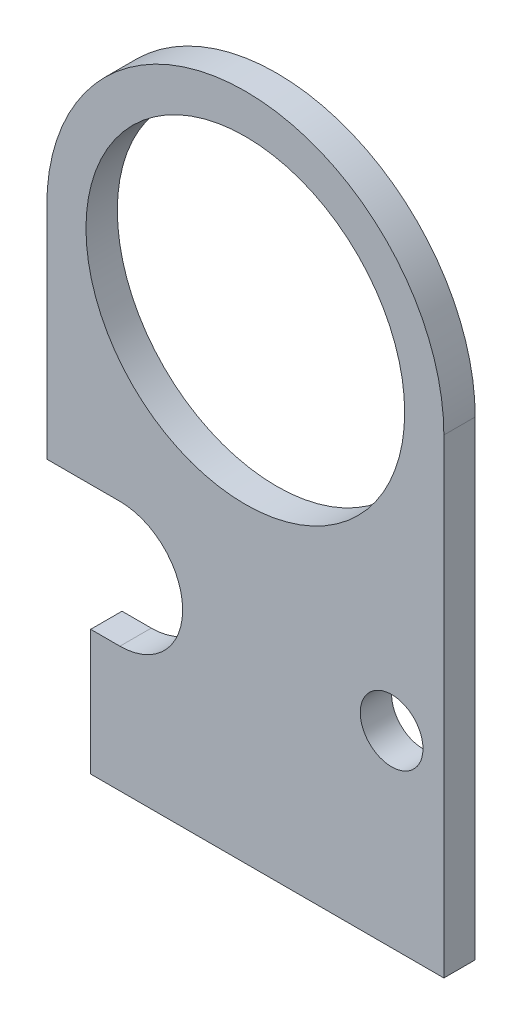
SolidWorks part; units mm, degrees
material "Foam"
ref_plane "Front Plane" through (0, 0, 0) normal (0, 0, 1) x (1, 0, 0)
ref_plane "Top Plane" through (0, 0, 0) normal (0, 1, 0) x (1, 0, 0)
ref_plane "Right Plane" through (0, 0, 0) normal (1, 0, 0) x (0, 0, -1)
sketch "Sketch1" plane through (0, 0, 0) normal (0, 0, 1) x (1, 0, 0)
  line L0 (-19, 0) -> (-19, -32)
  line L1 (-14.8, -45) -> (19, -45)
  line L2 (19, -45) -> (19, 0)
  line L3 (0, 0) -> (0, -45) construction
  line L8 (-19, -32) -> (-14.8, -32)
  line L9 (-14.8, -32) -> (-14.8, -45)
  arc A0 (19, 0) -> (-19, 0) centre (0, 0) ccw
  circle A1 centre (0, 0) radius 2.5
  arc A2 (-19, 0) -> (19, 0) centre (0, 0) ccw construction
  circle A3 centre (-14, -27) radius 1.5
  circle A6 centre (14, -27) radius 1.5
  dimension "D3" = 38
  dimension "D4" = 18
  dimension "D2" = 45
  dimension "D8" = 5
  dimension "D1" = 3
  dimension "D5" = 5
  dimension "D6" = 5
  dimension "D11" = 4.2
  dimension "D12" = 13
extrude "Boss-Extrude1" add sketch "Sketch1" along normal blind 3
sketch "Sketch2" plane through (0, 0, 3) normal (0, 0, 1) x (1, 0, 0)
  line L0 (-12, -21) -> (-19, -21)
  line L1 (-19, 0) -> (-19, -32) construction
  line L2 (-19, -21) -> (-19, -32)
  line L3 (-19, -32) -> (-14.8, -32)
  line L4 (-12, -33) -> (-14.8, -33)
  line L5 (-14.8, -33) -> (-14.8, -32)
  circle A0 centre (0, 0) radius 15.25
  arc A1 (-12, -33) -> (-12, -21) centre (-12, -27) ccw
  circle A2 centre (14, -27) radius 3
  circle A3 centre (-14, -27) radius 1.5 construction
  circle A4 centre (-14, -27) radius 1.5 construction
  dimension "D1" = 30.5
  dimension "D2" = 12
  dimension "D3" = 6
  dimension "D4" = 2
extrude "Cut-Extrude1" cut sketch "Sketch2" against normal through all
